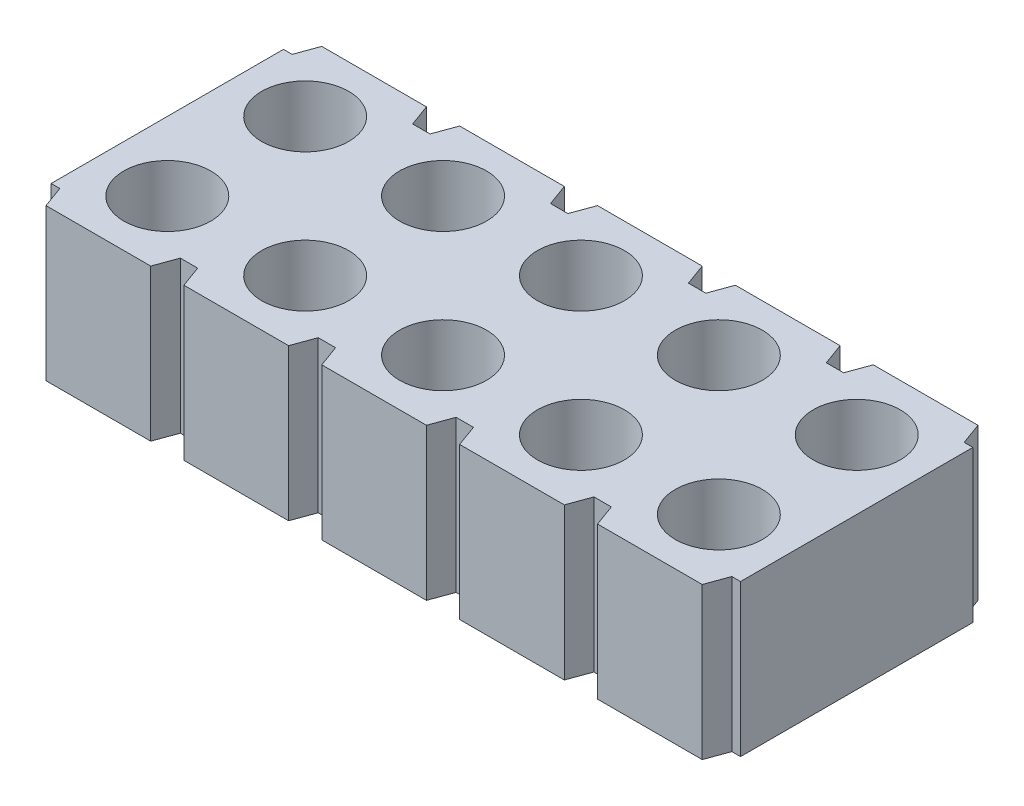
SolidWorks part; units mm, degrees
material "Nylon 46"
ref_plane "Front Plane" through (0, 0, 0) normal (0, 0, 1) x (1, 0, 0)
ref_plane "Top Plane" through (0, 0, 0) normal (0, 1, 0) x (1, 0, 0)
ref_plane "Right Plane" through (0, 0, 0) normal (1, 0, 0) x (0, 0, -1)
sketch "Sketch1" plane through (0, 0, 0) normal (0, 1, 0) x (1, 0, 0)
  line L0 (12.3944, 0.4) -> (12.2344, 0.4)
  line L1 (12.3944, 4.6799) -> (12.3944, 0.4)
  line L2 (-0.3056, 4.6799) -> (-0.1456, 4.6799)
  line L3 (-0.3056, 4.6799) -> (-0.3056, 0.4)
  line L4 (0, 0) -> (12.0887, 0)
  line L5 (0, 5.08) -> (-0.1456, 4.6799)
  line L6 (0, 0) -> (-0.1456, 0.4)
  line L7 (-0.3056, 0.4) -> (-0.1456, 0.4)
  line L9 (12.0887, 0) -> (12.2344, 0.4)
  line L10 (12.0887, 5.08) -> (12.2344, 4.6799)
  line L11 (12.3944, 4.6799) -> (12.2344, 4.6799)
  line L16 (12.0887, 5.08) -> (0, 5.08)
  dimension "D2" = 5.08
  dimension "D3" = 20
  dimension "D4" = 0.4
  dimension "D5" = 0.4
  dimension "D7" = 0.16
  dimension "INSLENGTH" = 12.7
extrude "Extrude1" add sketch "Sketch1" against normal blind 2.794
hole_wizard "Hole1" positions "3DSketch2" profile "Sketch3" legacy end condition through all
sketch3d "3DSketch2"
  line L4 (0, 0, 0) -> (12.0887, 0, 0) construction
  line L5 (-0.3056, 0, -4.6799) -> (-0.3056, 0, -0.4) construction
  point P0 (0.9644, 0, -1.27)
  dimension "D1" = 1.27
  dimension "D2" = 1.27
sketch "Sketch3" plane through (0.9644, 0, -1.27) normal (1, 0, 0) x (0, 0, 1)
  line L0 (0, 0) -> (0, 2.794)
  line L1 (0, 2.794) -> (0.8014, 2.794)
  line L2 (0.8014, 2.794) -> (0.8014, 0)
  line L3 (0.8014, 0) -> (0, 0)
  line L4 (0, 110) -> (0, -10) construction
  dimension "Diameter" = 1.6027
  dimension "Depth" = 2.794
sketch "Sketch4" plane through (0, 0, 0) normal (0, 1, 0) x (1, 0, 0)
  line L0 (1.9288, 0) -> (2.54, 0)
  line L2 (0, 0) -> (12.0887, 0) construction
  line L5 (2.0744, 0.4) -> (1.9288, 0)
  line L6 (2.3944, 0.4) -> (2.54, 0)
  line L7 (12.0887, 5.08) -> (0, 5.08) construction
  line L8 (2.0744, 0.4) -> (2.3944, 0.4)
  line L10 (2.0744, 4.6799) -> (2.3944, 4.6799)
  line L11 (2.3944, 4.6799) -> (2.54, 5.08)
  line L12 (2.0744, 4.6799) -> (1.9288, 5.08)
  line L13 (1.9288, 5.08) -> (2.54, 5.08)
  line L17 (-0.3056, 4.6799) -> (-0.3056, 0.4) construction
  dimension "D1" = 0.4
  dimension "D2" = 0.32
  dimension "D3" = 70
  dimension "D4" = 0.6112
  dimension "D5" = 0.4001
  dimension "D6" = 2.2344
extrude "Extrude2" cut sketch "Sketch4" against normal blind 2.794
pattern_linear "LPattern1" count 5 spacing 2.54 along (1, 0, 0) count 2 spacing 2.54 along (0, 0, -1) of "Hole1"
pattern_linear "LPattern2" count 35 spacing 2.54 along (1, 0, 0) of "Extrude2"
